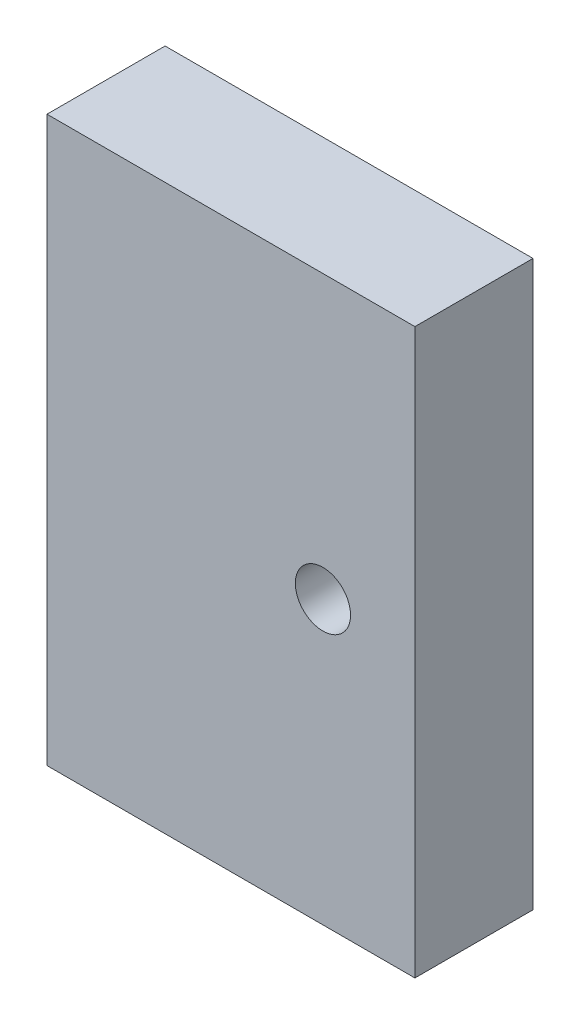
SolidWorks part; units mm, degrees
material "6061 Alloy"
ref_plane "Front Plane" through (0, 0, 0) normal (0, 0, 1) x (1, 0, 0)
ref_plane "Top Plane" through (0, 0, 0) normal (0, 1, 0) x (1, 0, 0)
ref_plane "Right Plane" through (0, 0, 0) normal (1, 0, 0) x (0, 0, -1)
sketch "Sketch1" plane through (0, 0, 0) normal (0, 0, 1) x (1, 0, 0)
  line L0 (15, 23) -> (-15, 23)
  line L1 (-15, 23) -> (15, 23) construction
  line L2 (-15, 23) -> (-15, -23)
  line L3 (-15, -23) -> (15, -23)
  line L4 (15, 23) -> (15, -23)
  line L5 (0, -23) -> (0, -3) construction
  line L6 (-15, 0) -> (15, 0) construction
  point P0 (0, 0)
  dimension "D1" = 30
  dimension "D2" = 46
  dimension "D3" = 3
extrude "3/8" add sketch "Sketch1" along normal blind 9.63
sketch "Sketch3" plane through (0, -23, 0) normal (0, -1, 0) x (1, 0, 0)
  circle A4 centre (-1.9899, 4.7875) radius 1.75
  circle A5 centre (10.0054, 4.7875) radius 1.75
  point P14 (0, 0)
  point P15 (0, 0)
extrude "M4_DRILL" cut sketch "Sketch3" against normal blind 8
sketch "Sketch5" plane through (0, 0, 9.63) normal (0, 0, 1) x (1, 0, 0)
  circle A1 centre (7.5, 0) radius 2.25
extrude "Cut-Extrude1" cut sketch "Sketch5" against normal blind 10
